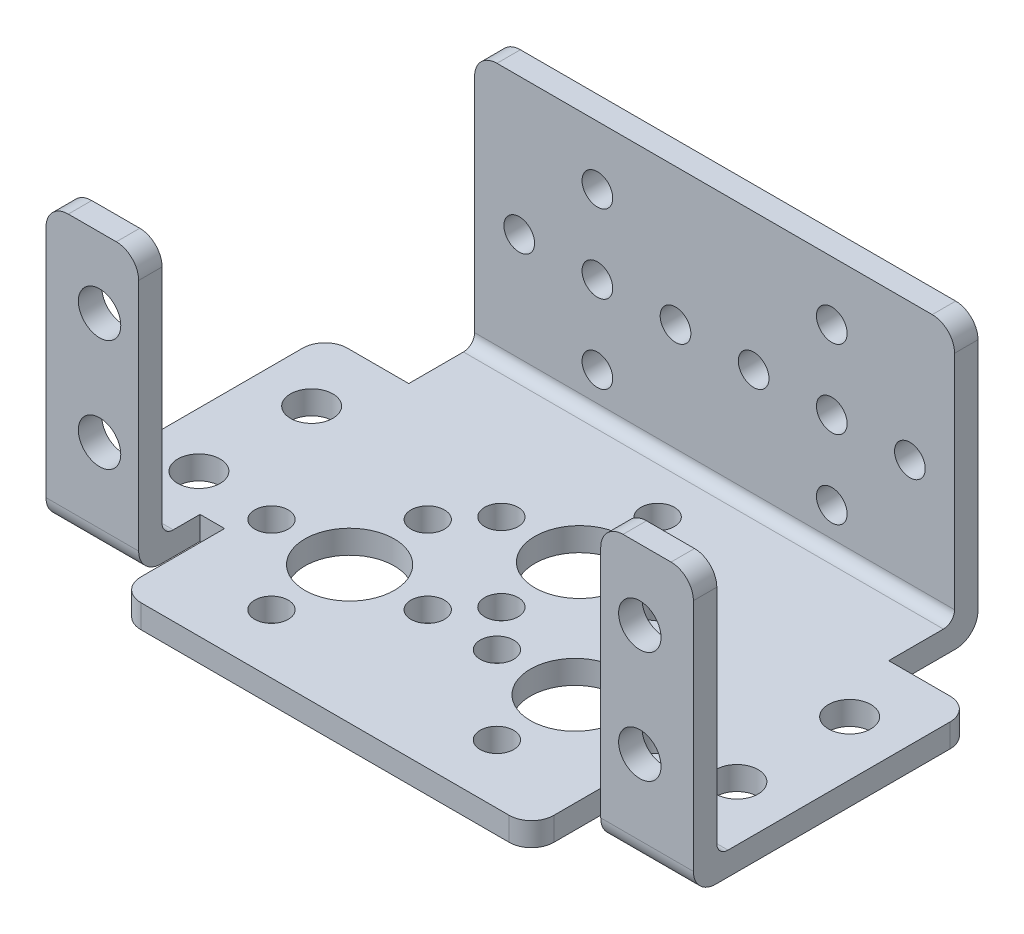
SolidWorks part; units mm, degrees
ref_plane "Front Plane" through (0, 0, 0) normal (0, 0, 1) x (1, 0, 0)
ref_plane "Top Plane" through (0, 0, 0) normal (0, 1, 0) x (1, 0, 0)
ref_plane "Right Plane" through (0, 0, 0) normal (1, 0, 0) x (0, 0, -1)
sketch "Sketch1" plane through (0, 0, 0) normal (0, 0, 1) x (1, 0, 0)
  line L1 (-29, -12.5) -> (29, -12.5)
  line L2 (-29, -12.5) -> (-29, 12.5)
  line L3 (-29, 12.5) -> (29, 12.5)
  line L4 (29, -12.5) -> (29, 12.5)
  line L5 (-29, -12.5) -> (29, 12.5) construction
  line L6 (-29, 12.5) -> (29, -12.5) construction
  point P0 (0, 0)
  dimension "D1" = 58
  dimension "D2" = 25
extrude "Boss-Extrude1" add sketch "Sketch1" along normal blind 37
sketch "Sketch2" plane through (-29, 0, 0) normal (-1, 0, 0) x (0, 0, 1)
  line L0 (37, 12.5) -> (0, 12.5) construction
  line L1 (2.1, 12.5) -> (30.9, 12.5)
  line L2 (2.1, 12.5) -> (2.1, -10.4)
  line L3 (2.1, -10.4) -> (30.9, -10.4)
  line L4 (30.9, 12.5) -> (30.9, -10.4)
  line L5 (0, 12.5) -> (0, -12.5) construction
  line L6 (37, -12.5) -> (0, -12.5) construction
  line L7 (37, 12.5) -> (37, -12.5) construction
  dimension "D1" = 2.1
  dimension "D2" = 2.1
  dimension "D3" = 6.1
extrude "Cut-Extrude1" cut sketch "Sketch2" against normal through all
sketch "Sketch3" plane through (0, 0, 37) normal (0, 0, 1) x (1, 0, 0)
  line L0 (29, 12.5) -> (-29, 12.5) construction
  line L1 (-20.3, 12.5) -> (20.3, 12.5)
  line L2 (-20.3, 12.5) -> (-20.3, -10.4)
  line L3 (-20.3, -10.4) -> (20.3, -10.4)
  line L4 (20.3, 12.5) -> (20.3, -10.4)
  line L5 (-29, -12.5) -> (29, -12.5) construction
  line L6 (-29, 12.5) -> (-29, -12.5) construction
  line L7 (29, -12.5) -> (29, 12.5) construction
  dimension "D1" = 2.1
  dimension "D2" = 8.7
  dimension "D3" = 8.7
extrude "Cut-Extrude2" cut sketch "Sketch3" against normal up to next
sketch "Sketch4" plane through (0, -12.5, 0) normal (0, -1, 0) x (1, 0, 0)
  line L1 (-29, 0) -> (-21.5, 0)
  line L2 (-29, 0) -> (-29, 8)
  line L3 (-29, 8) -> (-21.5, 8)
  line L4 (-21.5, 0) -> (-21.5, 8)
  line L5 (29, 0) -> (21.5, 0)
  line L6 (29, 0) -> (29, 8)
  line L7 (29, 8) -> (21.5, 8)
  line L8 (21.5, 0) -> (21.5, 8)
  dimension "D1" = 8
  dimension "D2" = 7.5
  dimension "D3" = 7.5
  dimension "D4" = 8
extrude "Cut-Extrude3" cut sketch "Sketch4" against normal through all
sketch "Sketch7" plane through (0, -12.5, 0) normal (0, -1, 0) x (1, 0, 0)
  line L1 (-29, 37) -> (-18.5, 37)
  line L2 (-29, 37) -> (-29, 33)
  line L3 (-29, 33) -> (-20.7, 33)
  line L4 (-18.5, 37) -> (-18.5, 33)
  line L5 (29, 37) -> (18.5, 37)
  line L6 (29, 37) -> (29, 33)
  line L7 (29, 33) -> (20.7, 33)
  line L8 (18.5, 37) -> (18.5, 33)
  line L10 (-18.5, 33) -> (-18.5, 27.5)
  line L11 (-18.5, 27.5) -> (-20.7, 27.5)
  line L12 (-20.7, 33) -> (-20.7, 27.5)
  line L14 (18.5, 33) -> (18.5, 27.5)
  line L15 (18.5, 27.5) -> (20.7, 27.5)
  line L16 (20.7, 33) -> (20.7, 27.5)
  dimension "D1" = 10.5
  dimension "D2" = 10.5
  dimension "D3" = 4
  dimension "D4" = 4
  dimension "D5" = 2.2
  dimension "D6" = 2.2
  dimension "D7" = 9.5
  dimension "D8" = 9.5
extrude "Cut-Extrude4" cut sketch "Sketch7" against normal through all
sketch "Sketch8" plane through (0, -10.4, 0) normal (0, 1, 0) x (-1, 0, 0)
  line L0 (0, 38.8401) -> (0, -3.117) construction
  line L1 (18.5, 37) -> (-18.5, 37) construction
  line L5 (-29, 8) -> (-29, 30.9) construction
  line L7 (29, 8) -> (29, 30.9) construction
  line L8 (21.5, 8) -> (29, 8) construction
  circle A0 centre (0, 14.2) radius 4
  circle A1 centre (7, 14.2) radius 1.5
  circle A2 centre (-7, 14.2) radius 1.5
  circle A3 centre (0, 7.2) radius 1.5
  circle A4 centre (0, 21.2) radius 1.5
  circle A7 centre (10.1, 24.7) radius 4
  circle A8 centre (17.1, 24.7) radius 1.5
  circle A9 centre (3.1, 24.7) radius 1.5
  circle A10 centre (10.1, 17.7) radius 1.5
  circle A11 centre (10.1, 31.7) radius 1.5
  circle A12 centre (-10.1, 24.7) radius 4
  circle A13 centre (-3.1, 24.7) radius 1.5
  circle A14 centre (-17.1, 24.7) radius 1.5
  circle A15 centre (-10.1, 17.7) radius 1.5
  circle A16 centre (-10.1, 31.7) radius 1.5
  circle A17 centre (24.1, 24.2) radius 1.9
  circle A18 centre (24.1, 14.1) radius 1.9
  circle A19 centre (-24.1, 14.1) radius 1.9
  circle A20 centre (-24.1, 24.2) radius 1.9
  dimension "D1" = 8
  dimension "D2" = 3
  dimension "D11" = 3.8
  dimension "D3" = 7
  dimension "D4" = 7
  dimension "D5" = 7
  dimension "D6" = 7
  dimension "D7" = 22.8
  dimension "D8" = 20.2
  dimension "D9" = 10.1
  dimension "D10" = 12.3
  dimension "D12" = 4.9
  dimension "D13" = 4.9
  dimension "D14" = 10.1
  dimension "D15" = 6.1
  dimension "D16" = 7
  dimension "D17" = 7
  dimension "D18" = 7
  dimension "D19" = 7
extrude "Cut-Extrude5" cut sketch "Sketch8" against normal through all
sketch "Sketch9" plane through (0, 0, 33) normal (0, 0, 1) x (1, 0, 0)
  line L0 (-29, 12.5) -> (-20.7, 12.5) construction
  line L1 (-29, 12.5) -> (-29, -12.5) construction
  line L2 (29, 12.5) -> (29, -12.5) construction
  circle A0 centre (-24.2, 6.2) radius 1.9
  circle A1 centre (-24.2, -3.8) radius 1.9
  circle A2 centre (24.2, 6.2) radius 1.9
  circle A3 centre (24.2, -3.8) radius 1.9
  dimension "D1" = 3.8
  dimension "D2" = 10
  dimension "D3" = 6.3
  dimension "D4" = 4.8
  dimension "D5" = 4.8
extrude "Cut-Extrude6" cut sketch "Sketch9" against normal up to next
sketch "Sketch10" plane through (0, 0, 0) normal (0, 0, -1) x (-1, 0, 0)
  line L0 (-21.5, 12.5) -> (21.5, 12.5) construction
  line L1 (0, 14.0161) -> (0, -13.408) construction
  circle A0 centre (-17.5, 0.22) radius 1.375
  circle A1 centre (-10.5, 0.22) radius 1.375
  circle A2 centre (-3.5, 0.22) radius 1.375
  circle A3 centre (3.5, 0.22) radius 1.375
  circle A4 centre (10.5, 0.22) radius 1.375
  circle A5 centre (17.5, 0.22) radius 1.375
  circle A6 centre (-10.5, 7.22) radius 1.375
  circle A7 centre (10.5, 7.22) radius 1.375
  circle A8 centre (-10.5, -6.78) radius 1.375
  circle A9 centre (10.5, -6.78) radius 1.375
  dimension "D1" = 2.75
  dimension "D2" = 12.28
  dimension "D3" = 7
  dimension "D4" = 7
  dimension "D5" = 7
  dimension "D6" = 7
  dimension "D7" = 7
  dimension "D8" = 3.5
  dimension "D9" = 7
  dimension "D10" = 7
extrude "Cut-Extrude7" cut sketch "Sketch10" against normal up to next
fillet "Fillet1" radius 2 13 edges at (0, -12.5, 0) (24.85, -12.5, 33) (-24.85, -12.5, 33) (-29, -11.45, 8) (29, -11.45, 8) (18.5, -11.45, 37) (-18.5, -11.45, 37) (-29, 12.5, 31.95) (-20.7, 12.5, 31.95) (20.7, 12.5, 31.95) (29, 12.5, 31.95) (21.5, 12.5, 1.05) (-21.5, 12.5, 1.05)
fillet "Fillet2" radius 1 3 edges at (-24.85, -10.4, 30.9) (24.85, -10.4, 30.9) (0, -10.4, 2.1)
